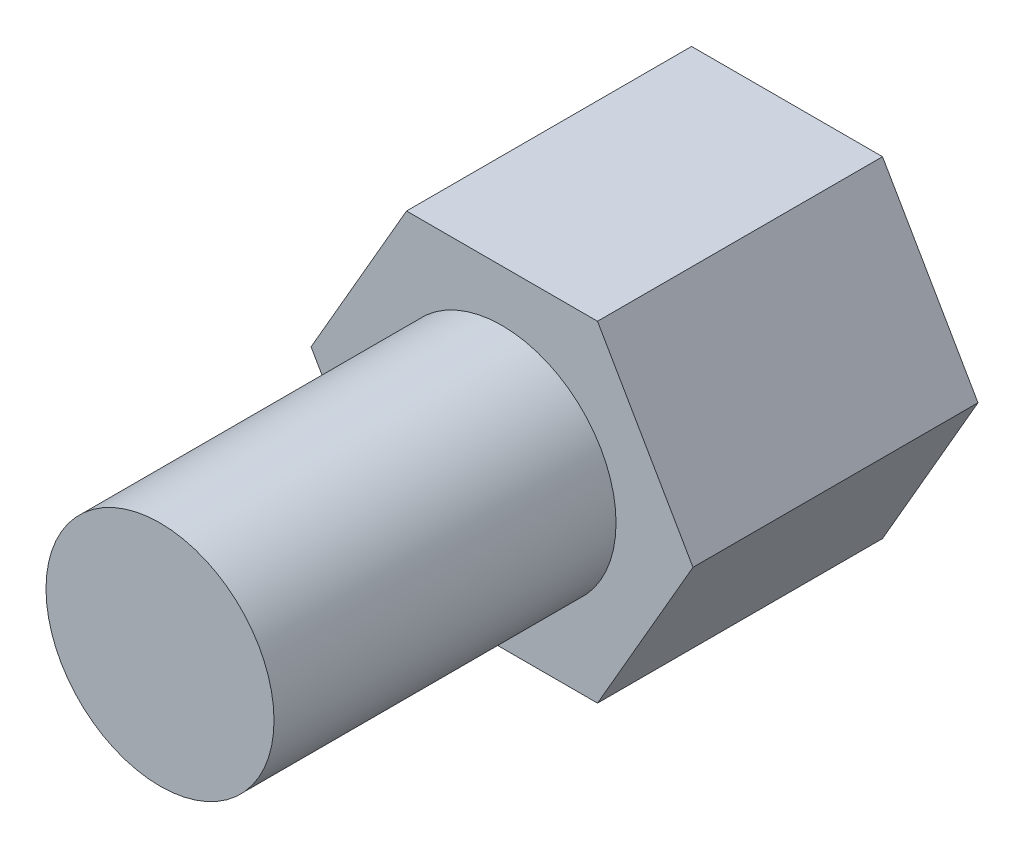
SolidWorks part; units mm, degrees
material "黃銅"
ref_plane "前基準面" through (0, 0, 0) normal (0, 0, 1) x (1, 0, 0)
ref_plane "上基準面" through (0, 0, 0) normal (0, 1, 0) x (1, 0, 0)
ref_plane "右基準面" through (0, 0, 0) normal (1, 0, 0) x (0, 0, -1)
sketch "草圖1" plane through (0, 0, 0) normal (0, 0, 1) x (1, 0, 0)
  line L1 (-1.675, 2.9012) -> (-3.35, 0)
  line L2 (-3.35, 0) -> (-1.675, -2.9012)
  line L3 (-1.675, -2.9012) -> (1.675, -2.9012)
  line L4 (1.675, -2.9012) -> (3.35, 0)
  line L5 (3.35, 0) -> (1.675, 2.9012)
  line L6 (1.675, 2.9012) -> (-1.675, 2.9012)
  circle A0 centre (0, 0) radius 2.9012 construction
  dimension "D1" = 6.7
extrude "填料-伸長1" add sketch "草圖1" along normal blind 5
sketch "草圖2" plane through (0, 0, 5) normal (0, 0, 1) x (1, 0, 0)
  circle A0 centre (0, 0) radius 2
  dimension "D1" = 4
extrude "填料-伸長2" add sketch "草圖2" along normal blind 6
sketch "草圖3" plane through (0, 0, 0) normal (0, 0, -1) x (-1, 0, 0)
  circle A0 centre (0, 0) radius 1.65
  dimension "D1" = 3.3
extrude "除料-伸長1" cut sketch "草圖3" against normal blind 3
